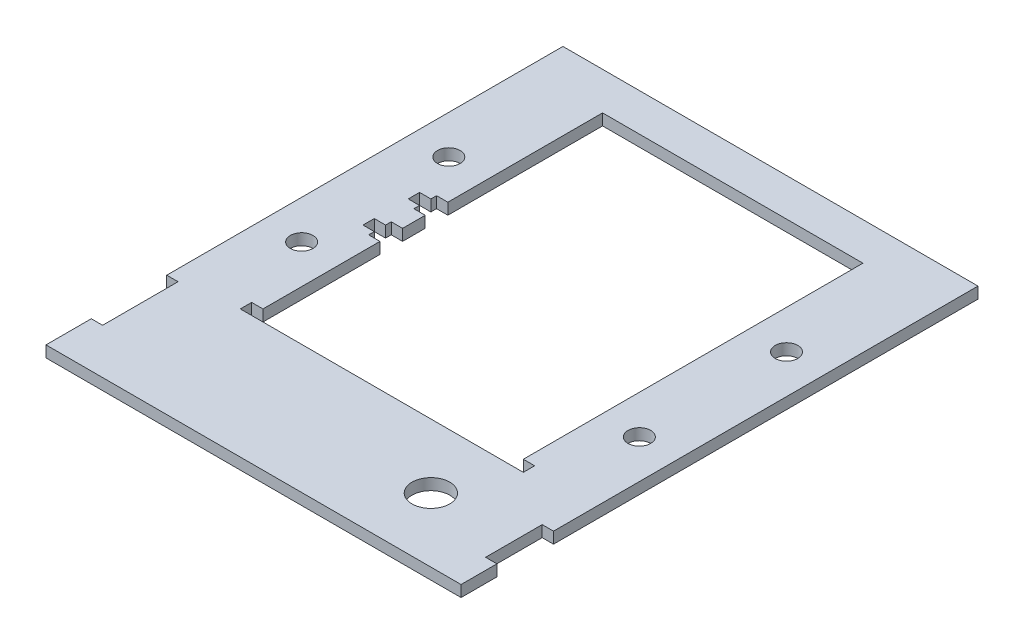
SolidWorks part; units mm, degrees
ref_plane "Alzado" through (0, 0, 0) normal (0, 0, 1) x (1, 0, 0)
ref_plane "Planta" through (0, 0, 0) normal (0, 1, 0) x (1, 0, 0)
ref_plane "Vista lateral" through (0, 0, 0) normal (1, 0, 0) x (0, 0, -1)
sketch "Croquis1" plane through (0, 0, 0) normal (0, 1, 0) x (1, 0, 0)
  line L0 (99.75, 99.5) -> (99.75, 60.5) construction
  line L1 (110, 3) -> (110, 12.5)
  line L2 (89.5, 37) -> (20.5, 37)
  line L3 (3, 20) -> (3, 15)
  line L4 (110, 27.5) -> (110, 37)
  line L5 (89.5, 71) -> (89.5, 89)
  line L6 (110, 3) -> (110, 12.5)
  line L7 (110, 140) -> (89.5, 140)
  line L8 (14.5, 86) -> (10.25, 86) construction
  line L9 (107, 12.5) -> (110, 12.5)
  line L10 (107, 27.5) -> (110, 27.5)
  line L11 (107, 20) -> (107, 12.5)
  line L12 (20.5, 140) -> (89.5, 140)
  line L13 (89.5, 130) -> (20.5, 130)
  line L14 (110, 27.5) -> (110, 140)
  line L15 (0, 50) -> (0, 35)
  line L16 (17.5, 87.5) -> (14.5, 87.5)
  line L17 (0, 15) -> (0, 3)
  line L18 (3, 35) -> (0, 35)
  line L19 (3, 15) -> (0, 15)
  line L20 (20.5, 37) -> (17.5, 37)
  line L21 (17.5, 37) -> (17.5, 40)
  line L22 (107, 20) -> (107, 27.5)
  line L23 (0, 140) -> (20.5, 140)
  line L24 (3, 20) -> (3, 35)
  line L25 (55, 130) -> (55, 37) construction
  line L26 (17.5, 40) -> (20.5, 40)
  line L27 (14.5, 87.5) -> (14.5, 84.5)
  line L28 (92.5, 40) -> (89.5, 40)
  line L29 (92.5, 37) -> (92.5, 40)
  line L30 (0, 50) -> (0, 140)
  line L31 (89.5, 37) -> (92.5, 37)
  line L32 (110, 3) -> (0, 3)
  line L33 (17.5, 84.5) -> (14.5, 84.5)
  line L34 (89.5, 89) -> (89.5, 130)
  line L35 (89.5, 71) -> (89.5, 40)
  line L36 (17.5, 87.5) -> (17.5, 89)
  line L37 (17.5, 72.5) -> (14.5, 72.5)
  line L38 (14.5, 72.5) -> (14.5, 75.5)
  line L39 (10.25, 80) -> (20.5, 80) construction
  line L40 (10.25, 99.5) -> (10.25, 60.5) construction
  line L41 (20.5, 77) -> (17.5, 77)
  line L42 (17.5, 71) -> (20.5, 71)
  line L43 (20.5, 71) -> (20.5, 40)
  line L44 (20.5, 89) -> (20.5, 130)
  line L45 (17.5, 89) -> (20.5, 89)
  line L46 (17.5, 40) -> (20.5, 40)
  line L47 (20.5, 83) -> (17.5, 83)
  line L48 (20.5, 77) -> (20.5, 83)
  line L49 (17.5, 77) -> (17.5, 75.5)
  line L50 (17.5, 83) -> (17.5, 84.5)
  line L51 (17.5, 75.5) -> (14.5, 75.5)
  line L52 (17.5, 72.5) -> (17.5, 71)
  circle A0 centre (99.75, 60.5) radius 3
  circle A1 centre (99.75, 99.5) radius 3
  circle A2 centre (10.25, 99.5) radius 3
  circle A3 centre (10.25, 60.5) radius 3
  circle A4 centre (85, 20) radius 5
  point P33 (55, 130)
  point P34 (55, 140)
  point P48 (14.5, 86)
  dimension "D7" = 6
  dimension "D9" = 6
  dimension "D36" = 6
  dimension "D37" = 6
  dimension "D38" = 10.25
  dimension "D44" = 10
  dimension "D1" = 15
  dimension "D2" = 3
  dimension "D3" = 20.5
  dimension "D4" = 57.5
  dimension "D5" = 39
  dimension "D6" = 5
  dimension "D8" = 3
  dimension "D10" = 3
  dimension "D11" = 6
  dimension "D12" = 3
  dimension "D13" = 3
  dimension "D14" = 1.5
  dimension "D15" = 3
  dimension "D16" = 1.5
  dimension "D17" = 6
  dimension "D18" = 3
  dimension "D19" = 6
  dimension "D20" = 3
  dimension "D21" = 31
  dimension "D22" = 3
  dimension "D23" = 34
  dimension "D24" = 12
  dimension "D25" = 3
  dimension "D26" = 110
  dimension "D27" = 15
  dimension "D28" = 90
  dimension "D29" = 69
  dimension "D30" = 18
  dimension "D31" = 41
  dimension "D32" = 69
  dimension "D33" = 69
  dimension "D34" = 20.5
  dimension "D35" = 20.5
  dimension "D39" = 9.5
  dimension "D40" = 7.5
  dimension "D41" = 7.5
  dimension "D42" = 9.5
  dimension "D43" = 1.5
  dimension "D45" = 17
  dimension "D46" = 30
extrude "Saliente-Extruir1" add sketch "Croquis1" along normal blind 3
